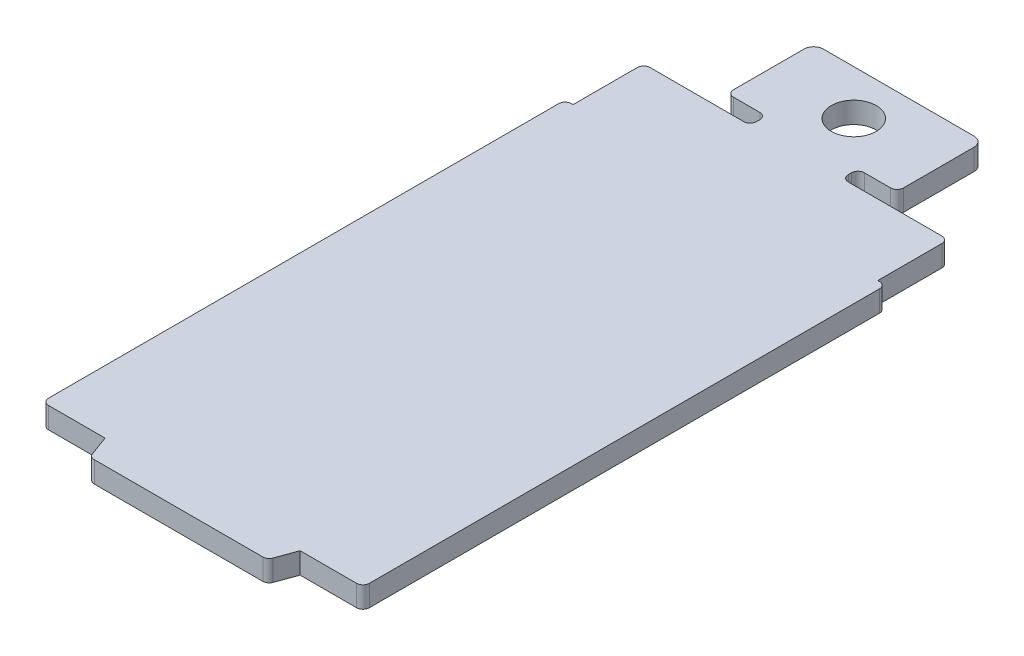
SolidWorks part; units mm, degrees
ref_plane "Front Plane" through (0, 0, 0) normal (0, 0, 1) x (1, 0, 0)
ref_plane "Top Plane" through (0, 0, 0) normal (0, 1, 0) x (1, 0, 0)
ref_plane "Right Plane" through (0, 0, 0) normal (1, 0, 0) x (0, 0, -1)
sketch "Sketch1" plane through (0, 0, 0) normal (0, 1, 0) x (1, 0, 0)
  line L0 (13.918, 224.0747) -> (13.918, -53.4203) construction
  line L1 (-15.927, 224.0747) -> (43.763, 224.0747)
  line L2 (-19.737, 220.2647) -> (-19.737, 192.3247)
  line L3 (-49.582, -51.5153) -> (-24.69, -51.5153)
  line L4 (47.573, 220.2647) -> (47.573, 192.3247)
  line L5 (-17.197, 189.7847) -> (-6.783, 189.7847)
  line L6 (-49.582, -51.5153) -> (-49.582, 180.8947)
  line L7 (45.033, 189.7847) -> (34.619, 189.7847)
  line L8 (-4.243, 187.2447) -> (-4.243, 185.9747)
  line L9 (-6.783, 183.4347) -> (-47.042, 183.4347)
  line L10 (32.079, 187.2447) -> (32.079, 185.9747)
  line L11 (34.619, 183.4347) -> (74.878, 183.4347)
  line L12 (77.418, -51.5153) -> (77.418, 180.8947)
  line L13 (52.526, -51.5153) -> (77.418, -51.5153)
  line L14 (-24.69, -51.5153) -> (-21.8315, -59.369)
  line L15 (-24.69, -51.5153) -> (-24.69, -61.0403) construction
  line L16 (-24.69, -61.0403) -> (52.526, -61.0403) construction
  line L17 (52.526, -51.5153) -> (52.526, -61.0403) construction
  line L18 (-19.4447, -61.0403) -> (47.2807, -61.0403)
  line L19 (49.6675, -59.369) -> (52.526, -51.5153)
  line L20 (-36.882, -13.4153) -> (64.718, -13.4153) construction
  line L30 (-19.737, 206.2947) -> (13.918, 206.2947) construction
  circle A0 centre (13.918, 206.2947) radius 8.89
  arc A1 (47.2807, -61.0403) -> (49.6675, -59.369) centre (47.2807, -58.5003) ccw
  arc A2 (-21.8315, -59.369) -> (-19.4447, -61.0403) centre (-19.4447, -58.5003) ccw
  arc A3 (-15.927, 224.0747) -> (-19.737, 220.2647) centre (-15.927, 220.2647) ccw
  arc A4 (43.763, 224.0747) -> (47.573, 220.2647) centre (43.763, 220.2647) cw
  arc A5 (32.079, 185.9747) -> (34.619, 183.4347) centre (34.619, 185.9747) ccw
  arc A6 (34.619, 189.7847) -> (32.079, 187.2447) centre (34.619, 187.2447) ccw
  arc A7 (47.573, 192.3247) -> (45.033, 189.7847) centre (45.033, 192.3247) cw
  arc A8 (-4.243, 185.9747) -> (-6.783, 183.4347) centre (-6.783, 185.9747) cw
  arc A9 (-6.783, 189.7847) -> (-4.243, 187.2447) centre (-6.783, 187.2447) cw
  arc A10 (-19.737, 192.3247) -> (-17.197, 189.7847) centre (-17.197, 192.3247) ccw
  arc A11 (77.418, 180.8947) -> (74.878, 183.4347) centre (74.878, 180.8947) ccw
  arc A12 (-49.582, 180.8947) -> (-47.042, 183.4347) centre (-47.042, 180.8947) cw
  point P24 (49.0592, -61.0403)
  point P27 (-21.2232, -61.0403)
  point P32 (32.079, 189.7847)
  point P40 (-4.243, 183.4347)
  point P43 (-4.243, 189.7847)
  point P47 (-19.737, 189.7847)
  point P52 (-49.582, 183.4347)
  dimension "D6" = 17.78
  dimension "D12" = 2.54
  dimension "D13" = 3.81
  dimension "D15" = 63.5
  dimension "D16" = 6.35
  dimension "D17" = 63.5
  dimension "D18" = 2.54
  dimension "D7" = 41.402
  dimension "D19" = 2.54
  dimension "D2" = 234.95
  dimension "D3" = 33.655
  dimension "D4" = 34.29
  dimension "D5" = 24.892
  dimension "D8" = 24.892
  dimension "D9" = 9.525
  dimension "D10" = 20
  dimension "D11" = 20
  dimension "D14" = 38.1
extrude "Boss-Extrude1" add sketch "Sketch1" along normal blind 8.382
sketch "Sketch15" plane through (0, 8.382, 0) normal (0, 1, 0) x (-1, 0, 0)
  line L0 (49.582, -180.8947) -> (49.582, 51.5153) construction
  line L1 (49.582, -155.4947) -> (46.407, -155.4947)
  line L2 (49.582, -155.4947) -> (49.582, -183.4347)
  line L3 (49.582, -183.4347) -> (46.407, -183.4347)
  line L4 (46.407, -155.4947) -> (46.407, -183.4347)
  line L5 (6.783, -183.4347) -> (47.042, -183.4347) construction
  line L6 (-77.418, 51.5153) -> (-77.418, -180.8947) construction
  line L7 (-77.418, -155.4947) -> (-74.243, -155.4947)
  line L8 (-77.418, -155.4947) -> (-77.418, -183.4347)
  line L9 (-77.418, -183.4347) -> (-74.243, -183.4347)
  line L10 (-74.243, -155.4947) -> (-74.243, -183.4347)
  line L11 (-74.878, -183.4347) -> (-34.619, -183.4347) construction
  dimension "D1" = 120.65
  dimension "D2" = 27.94
extrude "Cut-Extrude14" cut sketch "Sketch15" against normal through all
fillet "Fillet4" radius 2.54 6 edges at (77.418, 4.191, 51.5153) (-49.582, 4.191, 51.5153) (77.418, 4.191, -155.4947) (-49.582, 4.191, -155.4947) (74.243, 4.191, -183.4347) (-46.407, 4.191, -183.4347)
